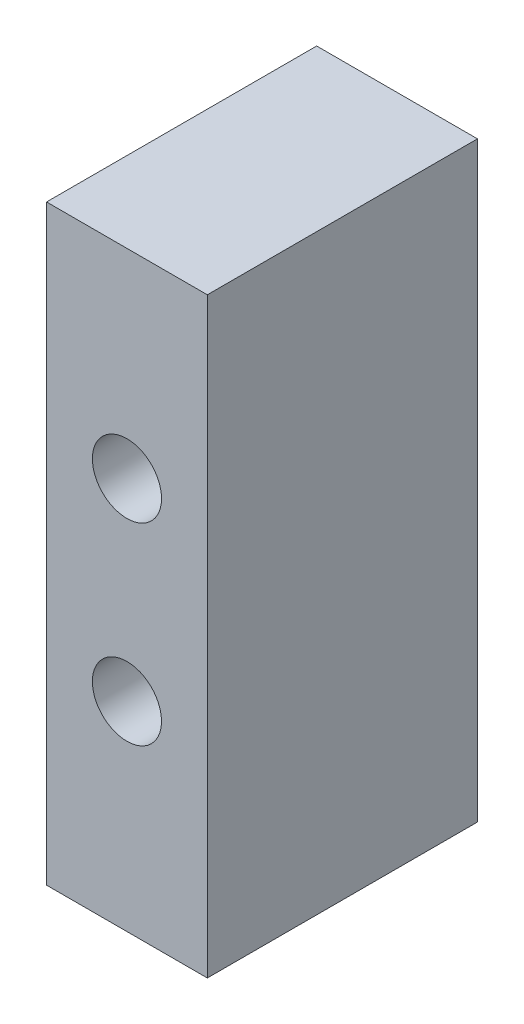
SolidWorks part; units mm, degrees
ref_plane "前视基准面" through (0, 0, 0) normal (0, 0, 1) x (1, 0, 0)
ref_plane "上视基准面" through (0, 0, 0) normal (0, 1, 0) x (1, 0, 0)
ref_plane "右视基准面" through (0, 0, 0) normal (1, 0, 0) x (0, 0, -1)
other "Configuration Table"
sketch "草图1" plane through (0, 0, 0) normal (0, 0, 1) x (1, 0, 0)
  line L0 (0, 0) -> (-21.1268, 0) construction
  line L1 (-5, 18.4) -> (5, 18.4)
  line L2 (-5, 18.4) -> (-5, -18.4)
  line L3 (-5, -18.4) -> (5, -18.4)
  line L4 (5, 18.4) -> (5, -18.4)
  line L5 (-5, 18.4) -> (5, -18.4) construction
  line L6 (-5, -18.4) -> (5, 18.4) construction
  circle A0 centre (0, 6) radius 2.15
  circle A1 centre (0, -6) radius 2.15
  point P0 (0, 0)
  dimension "D3" = 12
  dimension "D4" = 4.3
  dimension "D1" = 10
  dimension "D2" = 36.8
extrude "凸台-拉伸1" add sketch "草图1" along normal blind 16.8
